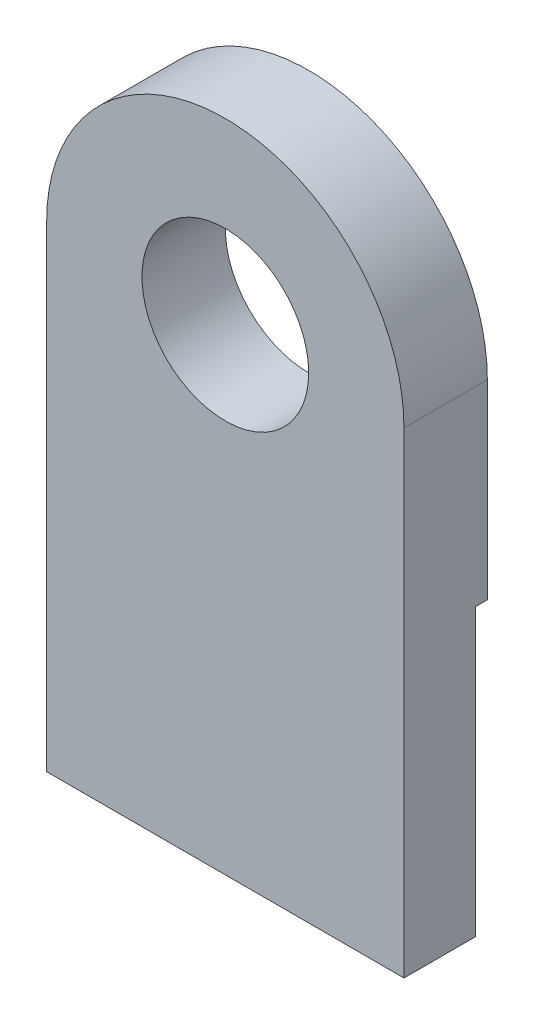
SolidWorks part; units mm, degrees
ref_plane "Front Plane" through (0, 0, 0) normal (0, 0, 1) x (1, 0, 0)
ref_plane "Top Plane" through (0, 0, 0) normal (0, 1, 0) x (1, 0, 0)
ref_plane "Right Plane" through (0, 0, 0) normal (1, 0, 0) x (0, 0, -1)
sketch "Sketch1" plane through (0, 0, 0) normal (0, 0, 1) x (1, 0, 0)
  line L0 (7.5, -14.7621) -> (7.5, 28.4379) construction
  line L1 (0, 0) -> (15, 0)
  line L2 (0, 0) -> (0, 12)
  line L3 (0, 12) -> (15, 12)
  line L4 (15, 0) -> (15, 12)
  line L5 (-7.6138, 6) -> (21.1862, 6) construction
  dimension "D1" = 12
  dimension "D2" = 15
extrude "Boss-Extrude1" add sketch "Sketch1" along normal blind 3
sketch "Sketch2" plane through (0, 0, 3) normal (0, 0, 1) x (1, 0, 0)
  line L0 (7.5, -14.3848) -> (7.5, 26.501) construction
  line L1 (18.5425, 6) -> (-4.971, 6) construction
  line L3 (0, 12) -> (15, 12)
  line L4 (0, 12) -> (0, 20)
  line L5 (0, 20) -> (15, 20)
  line L6 (15, 12) -> (15, 20)
  circle A0 centre (7.5, 20) radius 7.5
  circle A1 centre (7.5, 20) radius 3.5
  line M7 (15, 12) -> (0, 12)
  dimension "D1" = 15
  dimension "D3" = 7
  dimension "D2" = 20
extrude "Boss-Extrude2" add sketch "Sketch2" against normal blind 3.5 contours A0 L4 L6 M7 | A1 L5 A0 | A1 L5 A0
